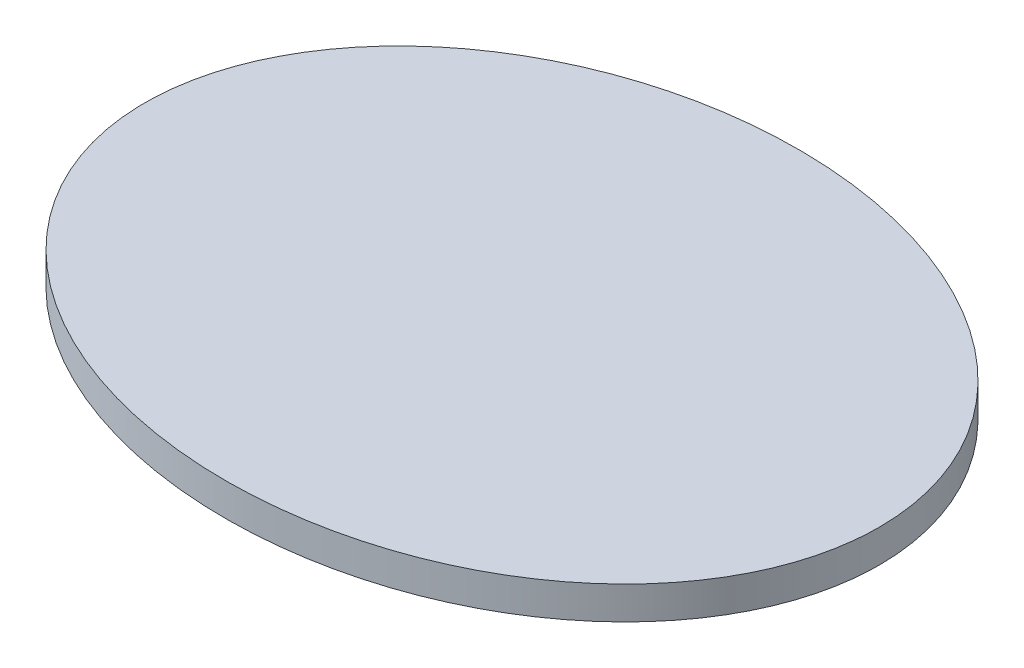
SolidWorks part; units mm, degrees
ref_plane "Front Plane" through (0, 0, 0) normal (0, 0, 1) x (1, 0, 0)
ref_plane "Top Plane" through (0, 0, 0) normal (0, 1, 0) x (1, 0, 0)
ref_plane "Right Plane" through (0, 0, 0) normal (1, 0, 0) x (0, 0, -1)
sketch "Sketch12" plane through (0, 0, 0) normal (0, 1, 0) x (1, 0, 0)
  ellipse E0 centre (0, 0) end of major axis (71.0556, 0) minor radius 55.4449
extrude "Boss-Extrude3" add sketch "Sketch12" along normal mid plane 6.35
sketch "Sketch13" plane through (0, 0, 0) normal (1, 0, 0) x (0, 0, -1)
  line L0 (-55.4449, 3.175) -> (-54.4398, 5.8339)
  line L1 (-54.4398, 5.8339) -> (-45.9303, 8.3367)
  line L2 (-41.5768, 26.6216) -> (-38.255, 35.8676)
  line L3 (-38.255, 35.8676) -> (-29.0781, 41.3737)
  line L4 (-29.0781, 41.3737) -> (-14.395, 41.3737)
  line L5 (4.401, 41.3737) -> (16.9735, 41.3737)
  line L6 (35.7695, 41.3737) -> (45.5055, 41.3737)
  line L7 (45.5055, 41.3737) -> (51.1785, 24.5215)
  line L8 (51.1785, 24.5215) -> (55.4449, 3.175)
  line L9 (55.4449, 3.175) -> (-55.4449, 3.175)
  arc A0 (-45.9303, 8.3367) -> (-41.5768, 26.6216) centre (-43.7535, 17.4792) ccw
  arc A1 (-14.395, 41.3737) -> (4.401, 41.3737) centre (-4.997, 41.3737) ccw
  arc A2 (16.9735, 41.3737) -> (35.7695, 41.3737) centre (26.3715, 41.3737) ccw
  dimension "D1" = 9.398
  dimension "D2" = 9.398
  dimension "D3" = 9.398
ref_plane "Plane2" through (12.7, 0, 0) normal (1, 0, 0) x (0, 0, -1)
ref_plane "Plane3" through (25.4, 0, 0) normal (1, 0, 0) x (0, 0, -1)
ref_plane "Plane4" through (38.1, 0, 0) normal (1, 0, 0) x (0, 0, -1)
ref_plane "Plane5" through (50.8, 0, 0) normal (1, 0, 0) x (0, 0, -1)
ref_plane "Plane6" through (63.5, 0, 0) normal (1, 0, 0) x (0, 0, -1)
